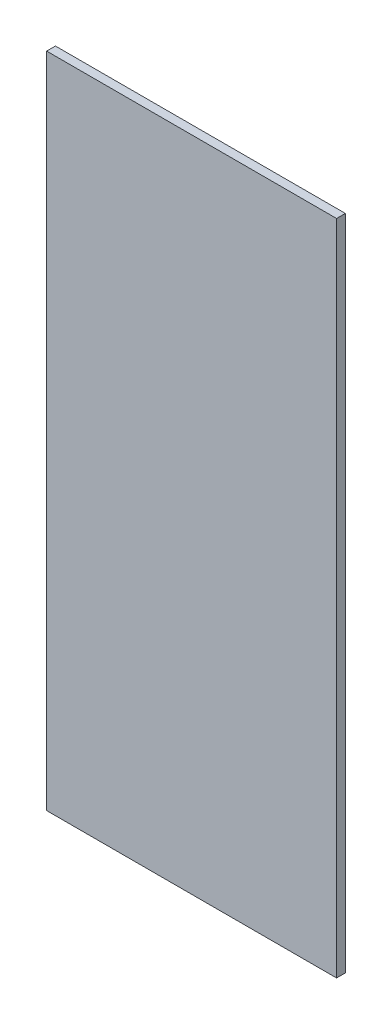
SolidWorks part; units mm, degrees
ref_plane "Front Plane" through (0, 0, 0) normal (0, 0, 1) x (1, 0, 0)
ref_plane "Top Plane" through (0, 0, 0) normal (0, 1, 0) x (1, 0, 0)
ref_plane "Right Plane" through (0, 0, 0) normal (1, 0, 0) x (0, 0, -1)
sketch "Sketch1" plane through (0, 0, 0) normal (0, 0, 1) x (1, 0, 0)
  line L0 (438.7482, -740) -> (1350, -740) construction
  line L1 (438.7482, -180) -> (438.7482, -1300) construction
  line L2 (1350, -765) -> (1350, -715) construction
  line L3 (1020, -1250) -> (1350, -1250) construction
  line L8 (1010, -365.6949) -> (680, -365.6949)
  line L9 (1010, -365.6949) -> (1010, -1114.3051)
  line L10 (1010, -1114.3051) -> (680, -1114.3051)
  line L11 (680, -365.6949) -> (680, -1114.3051)
  point P10 (1010, -740)
  dimension "D1" = 10
extrude "Boss-Extrude1" add sketch "Sketch1" along normal mid plane 10
